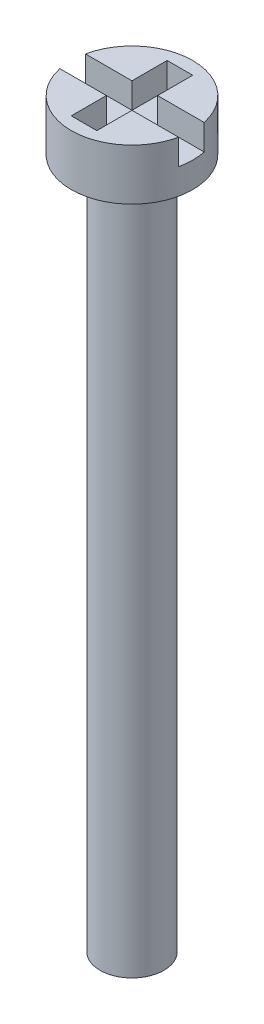
SolidWorks part; units mm, degrees
ref_plane "前视基准面" through (0, 0, 0) normal (0, 0, 1) x (1, 0, 0)
ref_plane "上视基准面" through (0, 0, 0) normal (0, 1, 0) x (1, 0, 0)
ref_plane "右视基准面" through (0, 0, 0) normal (1, 0, 0) x (0, 0, -1)
sketch "草图1" plane through (0, 0, 0) normal (0, 1, 0) x (1, 0, 0)
  circle A0 centre (0, 0) radius 1.25
  dimension "D1" = 2.5
extrude "拉伸1" add sketch "草图1" along normal blind 27
sketch "草图2" plane through (0, 27, 0) normal (0, 1, 0) x (-1, 0, 0)
  circle A0 centre (0, 0) radius 2.375
  dimension "D1" = 4.75
extrude "拉伸2" add sketch "草图2" along normal blind 2
sketch "草图3" plane through (0, 29, 0) normal (0, 1, 0) x (-1, 0, 0)
  line L0 (4.0624, 0) -> (-4.2778, 0) construction
  line L1 (0, -3.5166) -> (0, 3.738) construction
  line L3 (3.5023, -0.5) -> (-3.5023, -0.5)
  line L4 (3.5023, -0.5) -> (3.5023, 0.5)
  line L5 (3.5023, 0.5) -> (-3.5023, 0.5)
  line L6 (-3.5023, -0.5) -> (-3.5023, 0.5)
  dimension "D1" = 1
extrude "切除-拉伸1" cut sketch "草图3" against normal blind 1
sketch "草图4" plane through (0, 29, 0) normal (0, 1, 0) x (-1, 0, 0)
  line L0 (0, -3.8639) -> (0, 3.6765) construction
  line L1 (1.7727, 0) -> (-1.7019, 0) construction
  line L2 (0.5, -1.875) -> (-0.5, -1.875)
  line L3 (0.5, -1.875) -> (0.5, 1.875)
  line L4 (0.5, 1.875) -> (-0.5, 1.875)
  line L5 (-0.5, -1.875) -> (-0.5, 1.875)
  dimension "D1" = 1
  dimension "D2" = 3.75
extrude "切除-拉伸2" cut sketch "草图4" against normal blind 1
sketch "草图5" plane through (0, 0, 0) normal (1, 0, 0) x (0, 0, -1)
  line L0 (0, -2.1059) -> (0, 12.2815) construction
  line L1 (-0.5, 29) -> (-2.375, 29) construction
  line L2 (0, 10.9998) -> (-1.266, 10.9998)
  line L3 (-1.266, 17.1351) -> (-1.266, 10.9998)
  line L5 (0, 10.9998) -> (0, 29)
  arc A2 (0, 29) -> (-1.266, 17.1351) centre (0, 23) ccw
  dimension "D1" = 6
revolve "切除-旋转16" [suppressed] cut sketch "草图5" angle 360 about L0
